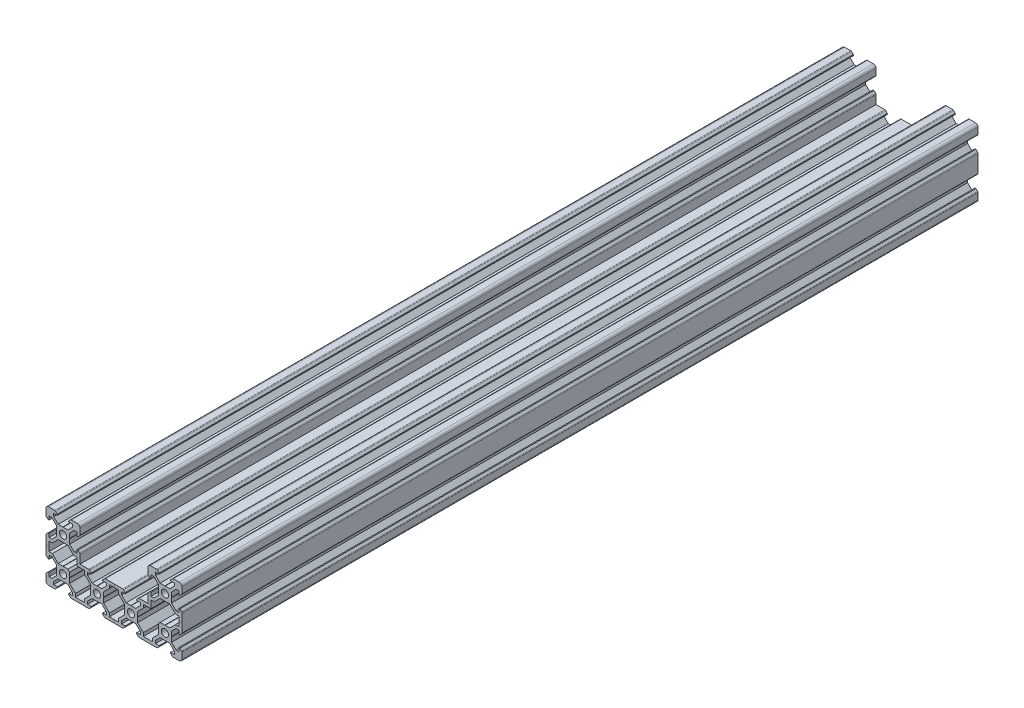
SolidWorks part; units mm, degrees
material "6063-T5"
ref_plane "Front" through (0, 0, 0) normal (0, 0, 1) x (1, 0, 0)
ref_plane "Top" through (0, 0, 0) normal (0, 1, 0) x (1, 0, 0)
ref_plane "Right" through (0, 0, 0) normal (1, 0, 0) x (0, 0, -1)
sketch "Sketch1" plane through (0, 0, 0) normal (0, 0, 1) x (1, 0, 0)
  line L0 (0, 32.3219) -> (0, -50.1713) construction
  line L1 (-2.8395, 3.9) -> (-0.1, 3.9)
  line L2 (-3.9, 2.8395) -> (-3.9, 0.1)
  line L3 (-2.8395, -3.9) -> (-0.1, -3.9)
  line L4 (3.9, 2.8395) -> (3.9, 0.1)
  line L5 (-29.7903, 0) -> (30, 0) construction
  line L6 (-0.1, -3.9) -> (0, -3.8)
  line L7 (-8.5, 10) -> (-4.8658, 10)
  line L8 (-10, 8.5) -> (-10, 4.8627)
  line L9 (-2.8395, -16.1) -> (-6.24, -12.6995)
  line L10 (10, 8.5) -> (10, 4.8627)
  line L11 (0, -3.8) -> (0.1, -3.9)
  line L12 (0.1, -3.9) -> (2.8395, -3.9)
  line L13 (-0.1, 3.9) -> (0, 3.8)
  line L14 (0, 3.8) -> (0.1, 3.9)
  line L15 (10, -10) -> (-10, 10) construction
  line L16 (-10, -10) -> (10, 10) construction
  line L17 (0.1, 3.9) -> (2.8395, 3.9)
  line L18 (-3.9, 0.1) -> (-3.8, 0)
  line L19 (-3.8, 0) -> (-3.9, -0.1)
  line L20 (-3.9, -0.1) -> (-3.9, -2.8395)
  line L21 (3.9, 0.1) -> (3.8, 0)
  line L22 (3.8, 0) -> (3.9, -0.1)
  line L23 (3.9, -0.1) -> (3.9, -2.8395)
  line L24 (0, -20) -> (58.4732, -20) construction
  line L25 (-3.9, 2.8395) -> (-6.561, 5.5005)
  line L26 (30, -50.1713) -> (30, 32.3219) construction
  line L27 (-5.5005, 8.2) -> (-3.3865, 8.2)
  line L28 (-8.2, 5.5005) -> (-8.2, 3.3865)
  line L29 (-10, -10) -> (-53.8942, -10) construction
  line L30 (8.2, 5.5005) -> (8.2, 3.3865)
  line L31 (-6.561, 5.5005) -> (-8.2, 5.5005)
  line L32 (-2.8395, 3.9) -> (-5.5005, 6.561)
  line L33 (-5.5005, 6.561) -> (-5.5005, 8.2)
  line L34 (6.561, 5.5005) -> (8.2, 5.5005)
  line L35 (3.9, 2.8395) -> (6.561, 5.5005)
  line L36 (5.5005, 6.561) -> (5.5005, 8.2)
  line L37 (2.8395, 3.9) -> (5.5005, 6.561)
  line L38 (6.561, -5.5005) -> (8.2, -5.5005)
  line L39 (-8.2, -12.6995) -> (-8.2, -7.3005)
  line L40 (2.8395, -3.9) -> (5.5005, -6.561)
  line L41 (3.9, -2.8395) -> (6.561, -5.5005)
  line L42 (-6.24, -12.6995) -> (-8.2, -12.6995)
  line L43 (-2.8395, -3.9) -> (-5.5005, -6.561)
  line L44 (-6.561, -5.5005) -> (-8.2, -5.5005)
  line L45 (-3.9, -2.8395) -> (-6.561, -5.5005)
  line L46 (30, -10) -> (10, -10) construction
  line L47 (-8.5, 10) -> (-10, 8.5) construction
  line L48 (8.5, 10) -> (10, 8.5) construction
  line L49 (-10, -10) -> (10, -30) construction
  line L50 (-5.5005, -6.561) -> (-6.24, -7.3005)
  line L51 (-3.9, -19.9) -> (-3.9, -17.1605)
  line L52 (-3.9, -17.1605) -> (-6.561, -14.4995)
  line L53 (10, 32.3219) -> (10, -50.1713) construction
  line L54 (-10, -30) -> (10, -10) construction
  line L55 (-4.3771, 9.7976) -> (-3.3865, 8.807)
  line L56 (-3.3865, 8.807) -> (-3.3865, 8.2)
  line L57 (4.3771, 9.7976) -> (3.3865, 8.807)
  line L58 (3.3865, 8.807) -> (3.3865, 8.2)
  line L59 (4.8658, 10) -> (8.5, 10)
  line L60 (3.3865, 8.2) -> (5.5005, 8.2)
  line L61 (-9.7968, 4.3732) -> (-8.807, 3.3865)
  line L62 (-8.807, 3.3865) -> (-8.2, 3.3865)
  line L63 (-9.7976, -4.3802) -> (-8.807, -3.3865)
  line L64 (-8.807, -3.3865) -> (-8.2, -3.3865)
  line L65 (9.7968, 4.3732) -> (8.807, 3.3865)
  line L66 (8.807, 3.3865) -> (8.2, 3.3865)
  line L67 (8.807, -3.3865) -> (8.2, -3.3865)
  line L68 (9.7976, -4.3802) -> (8.807, -3.3865)
  line L69 (-10, -4.87) -> (-10, -15.13)
  line L70 (-8.2, -3.3865) -> (-8.2, -5.5005)
  line L71 (10, -4.87) -> (10, -10)
  line L72 (8.2, -3.3865) -> (8.2, -5.5005)
  line L73 (-6.561, -14.4995) -> (-8.2, -14.4995)
  line L74 (-8.2, -16.6135) -> (-8.2, -14.4995)
  line L75 (-8.807, -16.6135) -> (-8.2, -16.6135)
  line L76 (-9.7976, -15.6198) -> (-8.807, -16.6135)
  line L77 (-10, -28.5) -> (-10, -24.8627)
  line L78 (-9.7968, -24.3732) -> (-8.807, -23.3865)
  line L79 (-8.807, -23.3865) -> (-8.2, -23.3865)
  line L80 (-8.2, -25.5005) -> (-8.2, -23.3865)
  line L81 (-6.561, -25.5005) -> (-8.2, -25.5005)
  line L82 (-3.9, -22.8395) -> (-6.561, -25.5005)
  line L83 (-3.9, -22.8395) -> (-3.9, -20.1)
  line L84 (-3.9, -20.1) -> (-3.8, -20)
  line L85 (-3.8, -20) -> (-3.9, -19.9)
  line L86 (0, -23.8) -> (0.1, -23.9)
  line L87 (-0.1, -23.9) -> (0, -23.8)
  line L88 (-2.8395, -23.9) -> (-0.1, -23.9)
  line L89 (0.1, -23.9) -> (2.8395, -23.9)
  line L90 (-2.8395, -23.9) -> (-5.5005, -26.561)
  line L91 (-5.5005, -28.2) -> (-3.3865, -28.2)
  line L92 (-5.5005, -26.561) -> (-5.5005, -28.2)
  line L93 (-4.3771, -29.7976) -> (-3.3865, -28.807)
  line L94 (-3.3865, -28.807) -> (-3.3865, -28.2)
  line L95 (-4.8658, -30) -> (-8.5, -30)
  line L96 (5.5005, -26.561) -> (5.5005, -28.2)
  line L97 (2.8395, -23.9) -> (5.5005, -26.561)
  line L98 (4.3771, -29.7976) -> (3.3865, -28.807)
  line L99 (3.3865, -28.807) -> (3.3865, -28.2)
  line L100 (3.3865, -28.2) -> (5.5005, -28.2)
  line L101 (4.8658, -30) -> (10, -30)
  line L102 (0.1, -16.1) -> (2.8395, -16.1)
  line L103 (0, -16.2) -> (0.1, -16.1)
  line L104 (-0.1, -16.1) -> (0, -16.2)
  line L105 (-2.8395, -16.1) -> (-0.1, -16.1)
  line L106 (3.9, -22.8395) -> (3.9, -20.1)
  line L107 (3.9, -20.1) -> (3.8, -20)
  line L108 (3.8, -20) -> (3.9, -19.9)
  line L109 (3.9, -19.9) -> (3.9, -17.1605)
  line L110 (3.9, -17.1605) -> (2.8395, -16.1)
  line L111 (-6.24, -7.3005) -> (-8.2, -7.3005)
  line L112 (6.24, -7.3005) -> (8.2, -7.3005)
  line L113 (5.5005, -6.561) -> (6.24, -7.3005)
  line L114 (12.6995, -28.2) -> (7.3005, -28.2)
  line L115 (7.3005, -28.2) -> (7.3005, -26.24)
  line L116 (7.3005, -26.24) -> (3.9, -22.8395)
  line L117 (16.1, -19.9) -> (16.1, -17.1605)
  line L118 (16.2, -20) -> (16.1, -19.9)
  line L119 (16.1, -20.1) -> (16.2, -20)
  line L120 (16.1, -22.8395) -> (16.1, -20.1)
  line L121 (20, -16.2) -> (19.9, -16.1)
  line L122 (20.1, -16.1) -> (20, -16.2)
  line L123 (22.8395, -16.1) -> (20.1, -16.1)
  line L124 (19.9, -16.1) -> (17.1605, -16.1)
  line L125 (23.9, -19.9) -> (23.9, -17.1605)
  line L126 (23.8, -20) -> (23.9, -19.9)
  line L127 (23.9, -20.1) -> (23.8, -20)
  line L128 (23.9, -22.8395) -> (23.9, -20.1)
  line L129 (20.1, -23.9) -> (20, -23.8)
  line L130 (22.8395, -23.9) -> (20.1, -23.9)
  line L131 (20, -23.8) -> (19.9, -23.9)
  line L132 (19.9, -23.9) -> (17.1605, -23.9)
  line L133 (12.6995, -28.2) -> (12.6995, -26.24)
  line L134 (14.4995, -26.561) -> (14.4995, -28.2)
  line L135 (17.1605, -23.9) -> (14.4995, -26.561)
  line L136 (12.6995, -26.24) -> (16.1, -22.8395)
  line L137 (16.6135, -28.807) -> (16.6135, -28.2)
  line L138 (16.6135, -28.2) -> (14.4995, -28.2)
  line L139 (15.6229, -29.7976) -> (16.6135, -28.807)
  line L140 (15.1342, -30) -> (10, -30)
  line L141 (20, 32.3219) -> (20, -50.1713) construction
  line L142 (10, -10) -> (30, -30) construction
  line L143 (30, -10) -> (10, -30) construction
  line L144 (27.3005, -28.2) -> (27.3005, -26.24)
  line L145 (25.5005, -26.561) -> (25.5005, -28.2)
  line L146 (24.3771, -29.7976) -> (23.3865, -28.807)
  line L147 (23.3865, -28.807) -> (23.3865, -28.2)
  line L148 (23.3865, -28.2) -> (25.5005, -28.2)
  line L149 (24.8658, -30) -> (30, -30)
  line L150 (27.3005, -28.2) -> (32.6995, -28.2)
  line L151 (25.5005, -26.561) -> (22.8395, -23.9)
  line L152 (27.3005, -26.24) -> (23.9, -22.8395)
  line L153 (25.5005, -13.439) -> (25.5005, -11.8)
  line L154 (27.3005, -11.8) -> (27.3005, -13.76)
  line L155 (27.3005, -13.76) -> (23.9, -17.1605)
  line L156 (25.5005, -13.439) -> (22.8395, -16.1)
  line L157 (12.6995, -11.8) -> (12.6995, -13.76)
  line L158 (14.4995, -13.439) -> (14.4995, -11.8)
  line L159 (17.1605, -16.1) -> (14.4995, -13.439)
  line L160 (16.1, -17.1605) -> (12.6995, -13.76)
  line L161 (23.3865, -11.193) -> (23.3865, -11.8)
  line L162 (16.6135, -11.193) -> (16.6135, -11.8)
  line L163 (16.6135, -11.8) -> (14.4995, -11.8)
  line L164 (23.3865, -11.8) -> (25.5005, -11.8)
  line L165 (15.6229, -10.2024) -> (16.6135, -11.193)
  line L166 (24.3771, -10.2024) -> (23.3865, -11.193)
  line L167 (24.8658, -10) -> (30, -10)
  line L168 (27.3005, -11.8) -> (32.6995, -11.8)
  line L169 (15.1342, -10) -> (10, -10)
  line L170 (12.6995, -11.8) -> (8.2, -11.8)
  line L171 (8.2, -11.8) -> (8.2, -7.3005)
  line L172 (60, -3.8) -> (59.9, -3.9)
  line L173 (60.1, -3.9) -> (60, -3.8)
  line L174 (63.8, 0) -> (63.9, -0.1)
  line L175 (63.9, 0.1) -> (63.8, 0)
  line L176 (56.1, 0.1) -> (56.2, 0)
  line L177 (56.2, 0) -> (56.1, -0.1)
  line L178 (60.1, 3.9) -> (60, 3.8)
  line L179 (60, 3.8) -> (59.9, 3.9)
  line L180 (62.8395, 3.9) -> (60.1, 3.9)
  line L181 (59.9, 3.9) -> (57.1605, 3.9)
  line L182 (63.9, 2.8395) -> (63.9, 0.1)
  line L183 (63.9, -0.1) -> (63.9, -2.8395)
  line L184 (62.8395, -3.9) -> (60.1, -3.9)
  line L185 (59.9, -3.9) -> (57.1605, -3.9)
  line L186 (56.1, -0.1) -> (56.1, -2.8395)
  line L187 (56.1, 2.8395) -> (56.1, 0.1)
  line L188 (60, -23.8) -> (59.9, -23.9)
  line L189 (60.1, -23.9) -> (60, -23.8)
  line L190 (60, -16.2) -> (59.9, -16.1)
  line L191 (60.1, -16.1) -> (60, -16.2)
  line L192 (63.8, -20) -> (63.9, -19.9)
  line L193 (63.9, -20.1) -> (63.8, -20)
  line L194 (56.2, -20) -> (56.1, -19.9)
  line L195 (56.1, -20.1) -> (56.2, -20)
  line L196 (40, -16.2) -> (40.1, -16.1)
  line L197 (39.9, -16.1) -> (40, -16.2)
  line L198 (36.2, -20) -> (36.1, -19.9)
  line L199 (36.1, -20.1) -> (36.2, -20)
  line L200 (43.8, -20) -> (43.9, -19.9)
  line L201 (43.9, -20.1) -> (43.8, -20)
  line L202 (40, -23.8) -> (40.1, -23.9)
  line L203 (39.9, -23.9) -> (40, -23.8)
  line L204 (56.1, -22.8395) -> (56.1, -20.1)
  line L205 (59.9, -23.9) -> (57.1605, -23.9)
  line L206 (62.8395, -23.9) -> (60.1, -23.9)
  line L207 (63.9, -22.8395) -> (63.9, -20.1)
  line L208 (63.9, -19.9) -> (63.9, -17.1605)
  line L209 (62.8395, -16.1) -> (60.1, -16.1)
  line L210 (59.9, -16.1) -> (57.1605, -16.1)
  line L211 (56.1, -19.9) -> (56.1, -17.1605)
  line L212 (43.9, -19.9) -> (43.9, -17.1605)
  line L213 (43.9, -22.8395) -> (43.9, -20.1)
  line L214 (40.1, -23.9) -> (42.8395, -23.9)
  line L215 (37.1605, -23.9) -> (39.9, -23.9)
  line L216 (36.1, -22.8395) -> (36.1, -20.1)
  line L217 (36.1, -19.9) -> (36.1, -17.1605)
  line L218 (37.1605, -16.1) -> (39.9, -16.1)
  line L219 (40.1, -16.1) -> (42.8395, -16.1)
  line L220 (42.8395, -23.9) -> (45.5005, -26.561)
  line L221 (47.3005, -26.24) -> (43.9, -22.8395)
  line L222 (43.9, -17.1605) -> (47.3005, -13.76)
  line L223 (42.8395, -16.1) -> (45.5005, -13.439)
  line L224 (34.4995, -13.439) -> (37.1605, -16.1)
  line L225 (32.6995, -13.76) -> (36.1, -17.1605)
  line L226 (34.4995, -26.561) -> (37.1605, -23.9)
  line L227 (32.6995, -26.24) -> (36.1, -22.8395)
  line L228 (47.3005, -11.8) -> (47.3005, -13.76)
  line L229 (45.5005, -13.439) -> (45.5005, -11.8)
  line L230 (47.3005, -28.2) -> (47.3005, -26.24)
  line L231 (45.5005, -26.561) -> (45.5005, -28.2)
  line L232 (34.4995, -26.561) -> (34.4995, -28.2)
  line L233 (32.6995, -28.2) -> (32.6995, -26.24)
  line L234 (34.4995, -13.439) -> (34.4995, -11.8)
  line L235 (32.6995, -11.8) -> (32.6995, -13.76)
  line L236 (43.3865, -28.2) -> (45.5005, -28.2)
  line L237 (43.3865, -28.807) -> (43.3865, -28.2)
  line L238 (44.3771, -29.7976) -> (43.3865, -28.807)
  line L239 (35.6229, -29.7976) -> (36.6135, -28.807)
  line L240 (36.6135, -28.807) -> (36.6135, -28.2)
  line L241 (36.6135, -28.2) -> (34.4995, -28.2)
  line L242 (44.3771, -10.2024) -> (43.3865, -11.193)
  line L243 (43.3865, -11.193) -> (43.3865, -11.8)
  line L244 (43.3865, -11.8) -> (45.5005, -11.8)
  line L245 (35.6229, -10.2024) -> (36.6135, -11.193)
  line L246 (36.6135, -11.193) -> (36.6135, -11.8)
  line L247 (36.6135, -11.8) -> (34.4995, -11.8)
  line L248 (35.1342, -30) -> (30, -30)
  line L249 (35.1342, -10) -> (30, -10)
  line L250 (51.8, -3.3865) -> (51.8, -5.5005)
  line L251 (51.193, -3.3865) -> (51.8, -3.3865)
  line L252 (50.2024, -4.3802) -> (51.193, -3.3865)
  line L253 (51.8, -11.8) -> (51.8, -7.3005)
  line L254 (50, -4.87) -> (50, -10)
  line L255 (44.8658, -10) -> (50, -10)
  line L256 (47.3005, -11.8) -> (51.8, -11.8)
  line L257 (62.8395, -16.1) -> (66.24, -12.6995)
  line L258 (63.9, -17.1605) -> (66.561, -14.4995)
  line L259 (63.9, -22.8395) -> (66.561, -25.5005)
  line L260 (62.8395, -23.9) -> (65.5005, -26.561)
  line L261 (57.1605, -23.9) -> (54.4995, -26.561)
  line L262 (52.6995, -26.24) -> (56.1, -22.8395)
  line L263 (63.9, 2.8395) -> (66.561, 5.5005)
  line L264 (62.8395, 3.9) -> (65.5005, 6.561)
  line L265 (57.1605, 3.9) -> (54.4995, 6.561)
  line L266 (56.1, 2.8395) -> (53.439, 5.5005)
  line L267 (63.9, -2.8395) -> (66.561, -5.5005)
  line L268 (62.8395, -3.9) -> (65.5005, -6.561)
  line L269 (57.1605, -3.9) -> (54.4995, -6.561)
  line L270 (56.1, -2.8395) -> (53.439, -5.5005)
  line L271 (64.3771, -29.7976) -> (63.3865, -28.807)
  line L272 (64.8658, -30) -> (68.5, -30)
  line L273 (65.5005, -28.2) -> (63.3865, -28.2)
  line L274 (55.6229, -29.7976) -> (56.6135, -28.807)
  line L275 (56.6135, -28.2) -> (54.4995, -28.2)
  line L276 (56.6135, -28.807) -> (56.6135, -28.2)
  line L277 (55.1342, -30) -> (50, -30)
  line L278 (44.8658, -30) -> (50, -30)
  line L279 (44.3771, -29.7976) -> (43.3865, -28.807)
  line L280 (43.3865, -28.807) -> (43.3865, -28.2)
  line L281 (43.3865, -28.2) -> (45.5005, -28.2)
  line L282 (47.3005, -28.2) -> (52.6995, -28.2)
  line L283 (70, -28.5) -> (70, -24.8627)
  line L284 (65.5005, -26.561) -> (65.5005, -28.2)
  line L285 (54.4995, -26.561) -> (54.4995, -28.2)
  line L286 (52.6995, -28.2) -> (52.6995, -26.24)
  line L287 (47.3005, -28.2) -> (47.3005, -26.24)
  line L288 (45.5005, -26.561) -> (45.5005, -28.2)
  line L289 (66.561, -5.5005) -> (68.2, -5.5005)
  line L290 (66.24, -7.3005) -> (68.2, -7.3005)
  line L291 (69.7976, -4.3802) -> (68.807, -3.3865)
  line L292 (68.807, -3.3865) -> (68.2, -3.3865)
  line L293 (68.2, -3.3865) -> (68.2, -5.5005)
  line L294 (68.2, -12.6995) -> (68.2, -7.3005)
  line L295 (70, -4.87) -> (70, -15.13)
  line L296 (69.7976, -15.6198) -> (68.807, -16.6135)
  line L297 (68.807, -16.6135) -> (68.2, -16.6135)
  line L298 (68.2, -16.6135) -> (68.2, -14.4995)
  line L299 (66.561, -14.4995) -> (68.2, -14.4995)
  line L300 (66.24, -12.6995) -> (68.2, -12.6995)
  line L301 (56.1, -17.1605) -> (57.1605, -16.1)
  line L302 (66.561, -25.5005) -> (68.2, -25.5005)
  line L303 (68.2, -25.5005) -> (68.2, -23.3865)
  line L304 (68.807, -23.3865) -> (68.2, -23.3865)
  line L305 (69.7968, -24.3732) -> (68.807, -23.3865)
  line L306 (53.76, -7.3005) -> (51.8, -7.3005)
  line L307 (53.439, -5.5005) -> (51.8, -5.5005)
  line L308 (54.4995, -6.561) -> (53.76, -7.3005)
  line L309 (65.5005, -6.561) -> (66.24, -7.3005)
  line L310 (54.4995, 6.561) -> (54.4995, 8.2)
  line L311 (56.6135, 8.2) -> (54.4995, 8.2)
  line L312 (56.6135, 8.807) -> (56.6135, 8.2)
  line L313 (55.6229, 9.7976) -> (56.6135, 8.807)
  line L314 (55.1342, 10) -> (51.5, 10)
  line L315 (50, 8.5) -> (50, 4.8627)
  line L316 (50.2032, 4.3732) -> (51.193, 3.3865)
  line L317 (51.193, 3.3865) -> (51.8, 3.3865)
  line L318 (51.8, 5.5005) -> (51.8, 3.3865)
  line L319 (53.439, 5.5005) -> (51.8, 5.5005)
  line L320 (66.561, 5.5005) -> (68.2, 5.5005)
  line L321 (68.2, 5.5005) -> (68.2, 3.3865)
  line L322 (68.807, 3.3865) -> (68.2, 3.3865)
  line L323 (69.7968, 4.3732) -> (68.807, 3.3865)
  line L324 (70, 8.5) -> (70, 4.8627)
  line L325 (68.5, 10) -> (64.8658, 10)
  line L326 (64.3771, 9.7976) -> (63.3865, 8.807)
  line L327 (63.3865, 8.807) -> (63.3865, 8.2)
  line L328 (65.5005, 8.2) -> (63.3865, 8.2)
  line L329 (65.5005, 6.561) -> (65.5005, 8.2)
  line L330 (63.3865, -28.807) -> (63.3865, -28.2)
  circle A0 centre (0, 0) radius 2.1
  circle A1 centre (0, -20) radius 2.1
  circle A2 centre (20, -20) radius 2.1
  circle A3 centre (60, 0) radius 2.1
  circle A4 centre (60, -20) radius 2.1
  circle A5 centre (40, -20) radius 2.1
  arc A6 (-8.5, 10) -> (-10, 8.5) centre (-8.5, 8.5) ccw
  arc A7 (10, 8.5) -> (8.5, 10) centre (8.5, 8.5) ccw
  arc A8 (-4.3771, 9.7976) -> (-4.8658, 10) centre (-4.8658, 9.3088) ccw
  arc A9 (4.3771, 9.7976) -> (4.8658, 10) centre (4.8658, 9.3088) cw
  arc A10 (-10, 4.8627) -> (-9.7968, 4.3732) centre (-9.3088, 4.8627) ccw
  arc A11 (9.7968, 4.3732) -> (10, 4.8627) centre (9.3088, 4.8627) ccw
  arc A12 (10, -4.87) -> (9.7976, -4.3802) centre (9.3062, -4.87) ccw
  arc A13 (-9.7976, -4.3802) -> (-10, -4.87) centre (-9.3062, -4.87) ccw
  arc A14 (-9.7976, -15.6198) -> (-10, -15.13) centre (-9.3062, -15.13) cw
  arc A15 (-8.5, -30) -> (-10, -28.5) centre (-8.5, -28.5) cw
  arc A16 (-10, -24.8627) -> (-9.7968, -24.3732) centre (-9.3088, -24.8627) cw
  arc A17 (-4.3771, -29.7976) -> (-4.8658, -30) centre (-4.8658, -29.3088) cw
  arc A18 (4.3771, -29.7976) -> (4.8658, -30) centre (4.8658, -29.3088) ccw
  arc A19 (15.6229, -29.7976) -> (15.1342, -30) centre (15.1342, -29.3088) cw
  arc A20 (24.3771, -29.7976) -> (24.8658, -30) centre (24.8658, -29.3088) ccw
  arc A21 (15.6229, -10.2024) -> (15.1342, -10) centre (15.1342, -10.6912) ccw
  arc A22 (24.3771, -10.2024) -> (24.8658, -10) centre (24.8658, -10.6912) cw
  arc A23 (44.3771, -29.7976) -> (44.8658, -30) centre (44.8658, -29.3088) ccw
  arc A24 (35.6229, -29.7976) -> (35.1342, -30) centre (35.1342, -29.3088) cw
  arc A25 (44.3771, -10.2024) -> (44.8658, -10) centre (44.8658, -10.6912) cw
  arc A26 (35.6229, -10.2024) -> (35.1342, -10) centre (35.1342, -10.6912) ccw
  arc A27 (50, -4.87) -> (50.2024, -4.3802) centre (50.6938, -4.87) cw
  arc A28 (64.3771, -29.7976) -> (64.8658, -30) centre (64.8658, -29.3088) ccw
  arc A29 (68.5, -30) -> (70, -28.5) centre (68.5, -28.5) ccw
  arc A30 (55.6229, -29.7976) -> (55.1342, -30) centre (55.1342, -29.3088) cw
  arc A31 (44.3771, -29.7976) -> (44.8658, -30) centre (44.8658, -29.3088) ccw
  arc A32 (69.7976, -4.3802) -> (70, -4.87) centre (69.3062, -4.87) cw
  arc A33 (69.7976, -15.6198) -> (70, -15.13) centre (69.3062, -15.13) ccw
  arc A34 (70, -24.8627) -> (69.7968, -24.3732) centre (69.3088, -24.8627) ccw
  arc A35 (55.6229, 9.7976) -> (55.1342, 10) centre (55.1342, 9.3088) ccw
  arc A36 (50, 8.5) -> (51.5, 10) centre (51.5, 8.5) cw
  arc A37 (50.2032, 4.3732) -> (50, 4.8627) centre (50.6912, 4.8627) cw
  arc A38 (70, 4.8627) -> (69.7968, 4.3732) centre (69.3088, 4.8627) cw
  arc A39 (68.5, 10) -> (70, 8.5) centre (68.5, 8.5) cw
  arc A40 (64.3771, 9.7976) -> (64.8658, 10) centre (64.8658, 9.3088) cw
  point P23 (-9.25, 9.25)
  point P69 (9.25, 9.25)
  point P188 (10, -28.2)
  point P223 (30, -28.2)
  point P320 (30, -11.8)
  dimension "D1" = 4.2
  dimension "D16" = 1.5
  dimension "D21" = 0.529
  dimension "D25" = 0.53
  dimension "D27" = 90
  dimension "D2" = 0.1
  dimension "D3" = 0.1
  dimension "D4" = 7.8
  dimension "D5" = 7.8
  dimension "D6" = 20
  dimension "D7" = 20
  dimension "D8" = 20
  dimension "D9" = 10
  dimension "D10" = 0.1
  dimension "D11" = 1.8
  dimension "D12" = 1.8
  dimension "D13" = 5.679
  dimension "D14" = 5.679
  dimension "D15" = 1.639
  dimension "D17" = 90
  dimension "D18" = 6.773
  dimension "D19" = 0.607
  dimension "D20" = 11.001
  dimension "D22" = 0.607
  dimension "D23" = 90
  dimension "D24" = 6.773
  dimension "D26" = 0.53
  dimension "D28" = 0.53
  dimension "D29" = 0.53
  dimension "D30" = 1.8
extrude "Boss-Extrude1" add sketch "Sketch1" along normal blind 468.54 contours A40 L326 L327 L328 L329 L264 L180 L178 L179 L181 L265 L310 L311 L312 L313 A35 L314 A36 L315 A37 L316 L317 L318 L319 L266 L187 L176 L177 L186 L270 L307 L250 L251 L252 A27 L254 L255 A25 L242 L243 L244 L229 L223 L219 L196 L197 L218 L224 L234 L247 L246
sketch "Sketch2" plane through (0, 0, 468.54) normal (0, 0, 1) x (1, 0, 0)
  line L0 (-10, -10) -> (70, -10)
  line L1 (-10, -4.87) -> (-10, -15.13) construction
  line L2 (70, -4.87) -> (70, -15.13) construction
split line "TopFixture1 - SplitLine"
sketch "Sketch3" plane through (0, 0, 0) normal (0, 0, -1) x (-1, 0, 0)
  line L0 (-70, -10) -> (10, -10)
  line L1 (-70, -4.87) -> (-70, -15.13) construction
  line L2 (10, -4.87) -> (10, -15.13) construction
split line "TopFixture2 - SplitLine"
sketch "Sketch6" plane through (0, 10, 0) normal (0, 1, 0) x (1, 0, 0)
  line L0 (-8.5, -234.27) -> (68.5, -234.27)
  line L1 (-8.5, -468.54) -> (-8.5, 0) construction
  line L2 (68.5, -468.54) -> (68.5, 0) construction
split line "TopFixture3 - SplitLine"
sketch "Sketch7" plane through (0, 0, 468.54) normal (0, 0, 1) x (1, 0, 0)
  line L0 (30, -30) -> (30, -10)
  line L1 (24.8658, -30) -> (35.1342, -30) construction
  line L2 (35.1342, -10) -> (24.8658, -10) construction
split line "SideFixture1 - SplitLine"
sketch "Sketch8" plane through (0, 0, 0) normal (0, 0, -1) x (-1, 0, 0)
  line L0 (-30, -10) -> (-30, -30)
  line L1 (-35.1342, -10) -> (-24.8658, -10) construction
  line L2 (-24.8658, -30) -> (-35.1342, -30) construction
split line "SideFixture2 - SplitLine"
sketch "Sketch9" plane through (-10, 0, 0) normal (-1, 0, 0) x (0, 0, 1)
  line L0 (234.27, -28.5) -> (234.27, 8.5)
  line L3 (468.54, -28.5) -> (0, -28.5) construction
  line L4 (468.54, 8.5) -> (0, 8.5) construction
split line "SideFixture3 - SplitLine"
equation "\"base-xwidth\" = 500mm"
equation "\"D1@Boss-Extrude1\"=\"base-xwidth\" -31.46mm"
